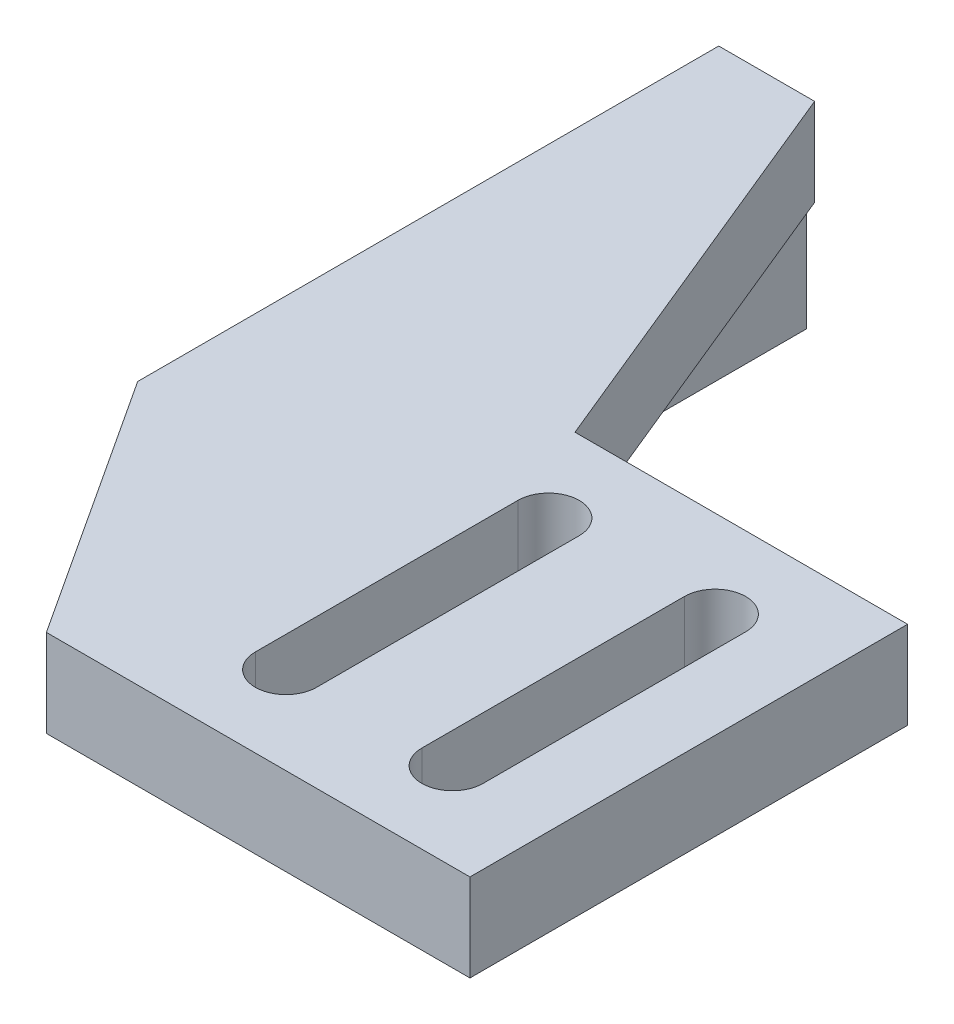
SolidWorks part; units mm, degrees
ref_plane "Piano frontale" through (0, 0, 0) normal (0, 0, 1) x (1, 0, 0)
ref_plane "Piano superiore" through (0, 0, 0) normal (0, 1, 0) x (1, 0, 0)
ref_plane "Piano destro" through (0, 0, 0) normal (1, 0, 0) x (0, 0, -1)
ref_plane "Piano1" through (0, 40, 0) normal (0, 1, 0) x (1, 0, 0)
sketch "Schizzo18" plane through (0, 40, 0) normal (0, 1, 0) x (1, 0, 0)
  line L0 (25, -16) -> (-9, -16)
  line L1 (25, -16) -> (25, 9)
  line L2 (25, 9) -> (6, 9)
  line L3 (-9, 32.2124) -> (-3.5247, 32.2124)
  line L4 (-9, -16) -> (-9, 32.2124)
  line L5 (-3.5247, 32.2124) -> (6, 9)
  line L6 (19, -16) -> (19, 9) construction
  line L7 (-9, -28.4145) -> (-9, 27.2974) construction
  line L8 (29.4558, 9) -> (-19.1855, 9) construction
  line L9 (25, -28.4145) -> (25, 27.2974) construction
  line L10 (29.4558, -16) -> (-19.1855, -16) construction
  line L11 (25, -11) -> (-9, -11) construction
  line L12 (25, 4) -> (-9, 4) construction
  line L13 (19, -11) -> (19, 4) construction
  line L14 (17.25, -11) -> (17.25, 4)
  line L15 (20.75, -11) -> (20.75, 4)
  line L16 (9.4906, -11) -> (9.4906, 4) construction
  line L17 (7.7406, -11) -> (7.7406, 4)
  line L18 (11.2406, -11) -> (11.2406, 4)
  arc A0 (17.25, -11) -> (20.75, -11) centre (19, -11) ccw
  arc A1 (20.75, 4) -> (17.25, 4) centre (19, 4) ccw
  arc A2 (7.7406, -11) -> (11.2406, -11) centre (9.4906, -11) ccw
  arc A3 (11.2406, 4) -> (7.7406, 4) centre (9.4906, 4) ccw
  point P22 (19, -3.5)
  point P29 (9.4906, -3.5)
  dimension "D6" = 15
  dimension "D1" = 6
  dimension "D2" = 25
  dimension "D3" = 34
  dimension "D4" = 5
  dimension "D5" = 15
extrude "Estrusione-Estrusione8" add sketch "Schizzo18" along normal blind 5 separate body
sketch "Schizzo19" plane through (0, 40, 0) normal (0, -1, 0) x (1, 0, 0)
  line L0 (-3.5247, -32.2124) -> (-9, -32.2124) construction
  line L1 (-9, 16) -> (-4, 16)
  line L2 (-9, 16) -> (-9, -32.2124)
  line L3 (-9, -32.2124) -> (-4, -32.2124)
  line L4 (-4, 16) -> (-4, -32.2124)
  dimension "D1" = 5
extrude "Estrusione-Estrusione9" add sketch "Schizzo19" along normal blind 6.5
sketch "Schizzo20" plane through (-9, 0, 0) normal (-1, 0, 0) x (0, 0, 1)
  line L0 (3.5, 45) -> (3.5, 33.5) construction
  line L1 (11, 45) -> (-4, 45) construction
  line L2 (16, 33.5) -> (-32.2124, 33.5) construction
  line L3 (-14.5, 45) -> (-14.5, 33.5) construction
  line L4 (-19.5, 45) -> (-19.5, 33.5) construction
  line L13 (-9.5, 45) -> (-9.5, 33.5) construction
  line L14 (-23.6103, 33.5) -> (25.3232, 33.5) construction
  line L15 (-23.6103, 36.5) -> (25.3232, 36.5) construction
  circle A0 centre (-19.5, 36.5) radius 1.75
  circle A1 centre (-9.5, 36.5) radius 1.75
  dimension "D1" = 18
  dimension "D2" = 5
  dimension "D3" = 5
  dimension "D4" = 3
extrude "Taglio-Estrusione9" cut sketch "Schizzo20" against normal blind 6
sketch "Schizzo21" plane through (-9, 0, 0) normal (-1, 0, 0) x (0, 0, 1)
  line L0 (16, 23.2712) -> (16, 48.2769) construction
  line L1 (1, 23.2712) -> (1, 48.2769) construction
  line L2 (16, 45) -> (16, 40.1473)
  dimension "D1" = 15
sketch "Schizzo24" plane through (0, 45, 0) normal (0, 1, 0) x (1, 0, 0)
  line L0 (-9, -16) -> (25, -16) construction
  line L2 (0.8051, -16) -> (-9, -0.979)
  line L3 (-9, 32.2124) -> (-9, -16) construction
  line L4 (-9, -0.979) -> (-9, -16)
  line L5 (-9, -16) -> (0.8051, -16)
extrude "Taglio-Estrusione13" cut sketch "Schizzo24" against normal blind 21
ref_plane "Piano2" through (0, 0, 0.979) normal (0, 0, 1) x (1, 0, 0)
sketch "Schizzo26" plane through (0, 0, 0.979) normal (0, 0, 1) x (1, 0, 0)
  line L0 (-9, 23.2712) -> (-9, 48.2769) construction
  line L1 (-4, 33.5) -> (-9, 33.5)
  line L2 (-4, 33.5) -> (-4, 40)
  line L3 (-4, 40) -> (-9, 40)
  line L4 (-9, 33.5) -> (-9, 40)
  line L5 (55, 40) -> (-55, 40) construction
extrude "Taglio-Estrusione15" cut sketch "Schizzo26" along normal blind 21
